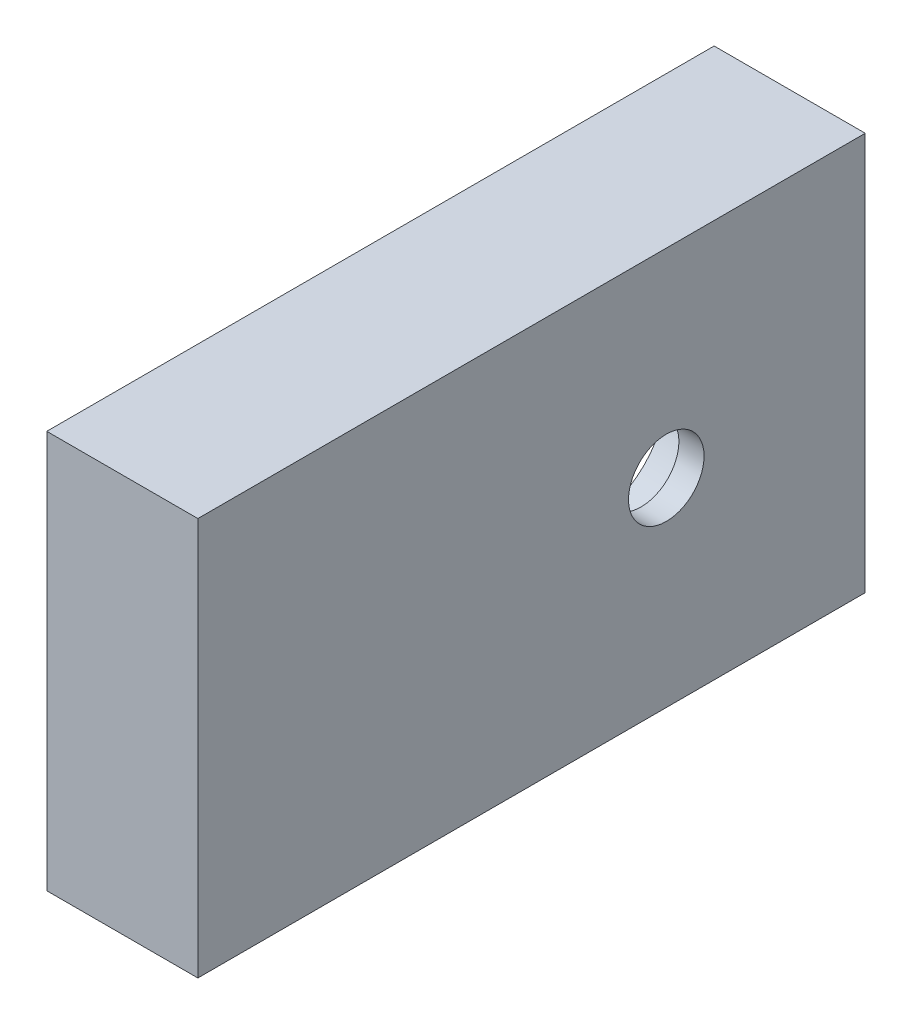
SolidWorks part; units mm, degrees
ref_plane "Front Plane" through (0, 0, 0) normal (0, 0, 1) x (1, 0, 0)
ref_plane "Top Plane" through (0, 0, 0) normal (0, 1, 0) x (1, 0, 0)
ref_plane "Right Plane" through (0, 0, 0) normal (1, 0, 0) x (0, 0, -1)
sketch "Sketch1" plane through (0, 0, 0) normal (1, 0, 0) x (0, 0, -1)
  line L0 (-16.6, 5.9) -> (5.9, 5.9)
  line L1 (-16.6, 5.9) -> (-16.6, -5.9)
  line L2 (-16.6, -5.9) -> (5.9, -5.9)
  line L3 (5.9, 5.9) -> (5.9, -5.9)
  line L4 (-18.6, 7.9) -> (7.9, 7.9)
  line L5 (7.9, 7.9) -> (7.9, -7.9)
  line L6 (-18.6, -7.9) -> (7.9, -7.9)
  line L7 (-18.6, 7.9) -> (-18.6, -7.9)
  circle A0 centre (0, 0) radius 1.5
  dimension "D1" = 3
  dimension "D2" = 2
extrude "Boss-Extrude1" add sketch "Sketch1" along normal blind 3 contours L4 L7 L6 L5 L0 L3 L2 L1
sketch "Sketch2" plane through (3, 0, 0) normal (1, 0, 0) x (0, 0, -1)
  line L1 (-18.6, 7.9) -> (7.9, 7.9)
  line L2 (-18.6, 7.9) -> (-18.6, -7.9)
  line L3 (-18.6, -7.9) -> (7.9, -7.9)
  line L4 (7.9, 7.9) -> (7.9, -7.9)
  circle A0 centre (0, 0) radius 1.5
  dimension "D1" = 3
extrude "Boss-Extrude2" add sketch "Sketch2" along normal blind 3
sketch "Sketch3" plane through (3, 0, 0) normal (-1, 0, 0) x (0, 0, 1)
  circle A0 centre (0, 0) radius 3
  dimension "D1" = 6
extrude "Cut-Extrude1" cut sketch "Sketch3" against normal blind 2
